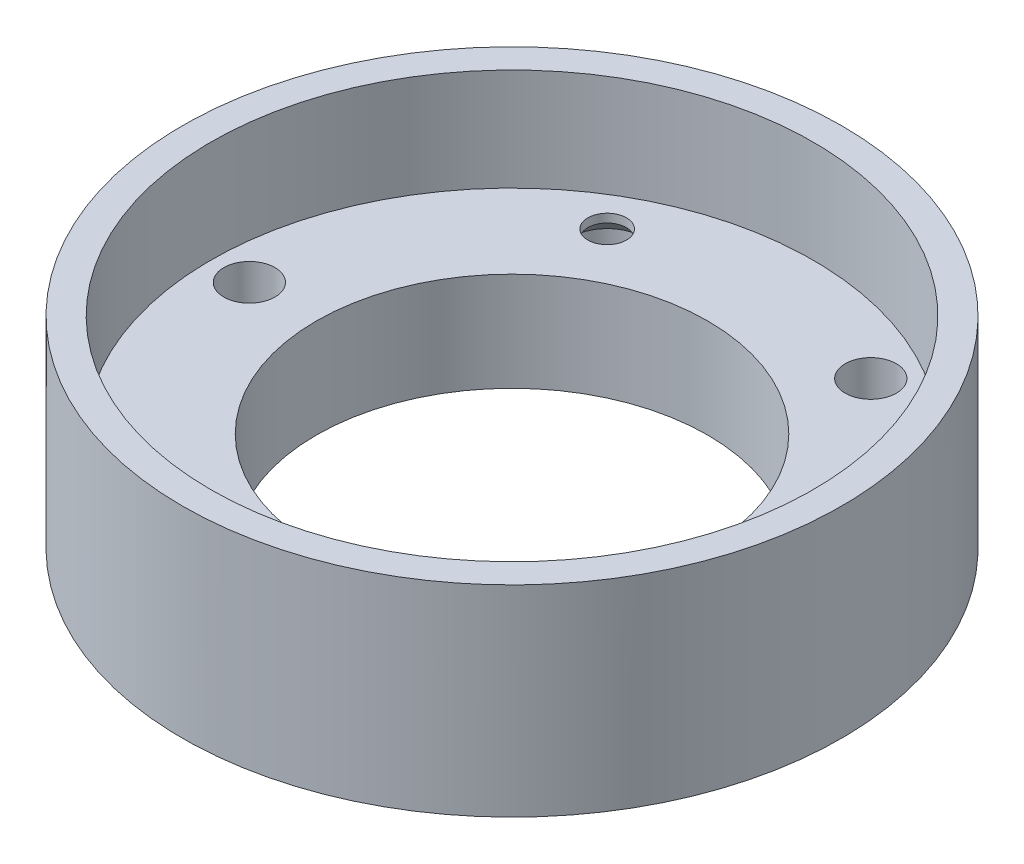
SolidWorks part; units mm, degrees
ref_plane "Plan de face" through (0, 0, 0) normal (0, 0, 1) x (1, 0, 0)
ref_plane "Plan de dessus" through (0, 0, 0) normal (0, 1, 0) x (1, 0, 0)
ref_plane "Plan de droite" through (0, 0, 0) normal (1, 0, 0) x (0, 0, -1)
sketch "Esquisse1" plane through (0, 0, 0) normal (0, 1, 0) x (1, 0, 0)
  circle A0 centre (0, 0) radius 29
  dimension "D1" = 58
extrude "Boss.-Extru.1" add sketch "Esquisse1" along normal blind 11.2
sketch "Esquisse2" plane through (0, 11.2, 0) normal (0, 1, 0) x (1, 0, 0)
  circle A0 centre (0, 0) radius 26.5
  circle A1 centre (0, 0) radius 29 construction
  dimension "D1" = 2.5
extrude "Enlèv. mat.-Extru.1" cut sketch "Esquisse2" against normal blind 9
sketch "Esquisse3" plane through (0, 2.2, 0) normal (0, 1, 0) x (1, 0, 0)
  circle A0 centre (0, 0) radius 17.225
  dimension "D1" = 34.45
extrude "Enlèv. mat.-Extru.2" cut sketch "Esquisse3" against normal through all contours A0
hole_wizard "Fraisage pour vis à tête fraisée M31" positions "Esquisse4" profile "Esquisse6" countersink size "M3" standard "Ansi Metric" end condition through all
sketch "Esquisse4" plane through (0, 0, 0) normal (0, -1, 0) x (-1, 0, 0)
  line L0 (-20.925, 0) -> (-17.225, 0) construction
  circle A0 centre (-22.875, 0) radius 1.95 construction
  circle A1 centre (0, 0) radius 17.225 construction
  point P0 (-22.875, 0)
  point P16 (11.4375, 19.8103)
  point P17 (11.4375, -19.8103)
  point P18 (0, 0)
  dimension "D1" = 3.9
  dimension "D2" = 3.7
  dimension "D3" = 3
sketch "Esquisse6" plane through (22.875, 0, 0) normal (1, 0, 0) x (0, 0, -1)
  line L0 (0, 0) -> (0, 11.2)
  line L1 (0, 11.2) -> (1.7, 11.2)
  line L2 (1.7, 11.2) -> (1.7, 1.45)
  line L3 (1.7, 1.45) -> (3.15, 0)
  line L5 (3.15, 0) -> (0, 0)
  line L6 (-1.7, 1.45) -> (-3.15, 0) construction
  line L11 (0, -6.35) -> (0, 107.95) construction
  dimension "Diamètre du perçage jusqu'au prochain" = 3.4
  dimension "Profondeur du perçage jusqu'au prochain" = 11.2
  dimension "Diamètre du fraisage entrant" = 6.3
  dimension "Angle du fraisage entrant" = 90
sketch "Esquisse7" plane through (0, 0, 0) normal (0, -1, 0) x (1, 0, 0)
  circle A1 centre (0, 0) radius 17.225
  circle A2 centre (0, 0) radius 17.225
  circle A3 centre (-11.4375, 19.8103) radius 3.15
  circle A4 centre (-11.4375, 19.8103) radius 3.15
  circle A5 centre (-11.4375, -19.8103) radius 3.15
  circle A6 centre (-11.4375, -19.8103) radius 3.15
  circle A7 centre (22.875, 0) radius 3.15
  circle A8 centre (22.875, 0) radius 3.15
  circle A9 centre (0, 0) radius 29
  circle A10 centre (0, 0) radius 29
  dimension "D1" = 0
  dimension "D2" = 0
  dimension "D3" = 0
  dimension "D4" = 0
  dimension "D5" = 0
extrude "Boss.-Extru.2" add sketch "Esquisse7" along normal blind 6.5
hole_wizard "Diamètre du perçage Ø4.5 (4.5)1" positions "Esquisse8" profile "Esquisse9" hole size "Ø4.5" standard "Ansi Metric" end condition through all
sketch "Esquisse8" plane through (0, -6.5, 0) normal (0, -1, 0) x (-1, 0, 0)
  line L1 (0, 0) -> (17.225, 0) construction
  line L2 (17.225, 0) -> (29, 0) construction
  circle A0 centre (0, 0) radius 17.225 construction
  circle A1 centre (0, 0) radius 29 construction
  point P14 (23.1125, 0)
  point P21 (-11.5562, -20.016)
  point P22 (-11.5562, 20.016)
  point P23 (0, 0)
  dimension "D1" = 3
sketch "Esquisse9" plane through (0, -6.5, 0) normal (1, 0, 0) x (0, 0, -1)
  line L0 (0, 0) -> (0, 17.7)
  line L1 (0, 17.7) -> (2.25, 17.7)
  line L2 (2.25, 17.7) -> (2.25, 0)
  line L5 (2.25, 0) -> (0, 0)
  line L11 (0, -6.35) -> (0, 107.95) construction
  dimension "Diamètre du perçage jusqu'au prochain" = 4.5
  dimension "Profondeur du perçage jusqu'au prochain" = 17.7
